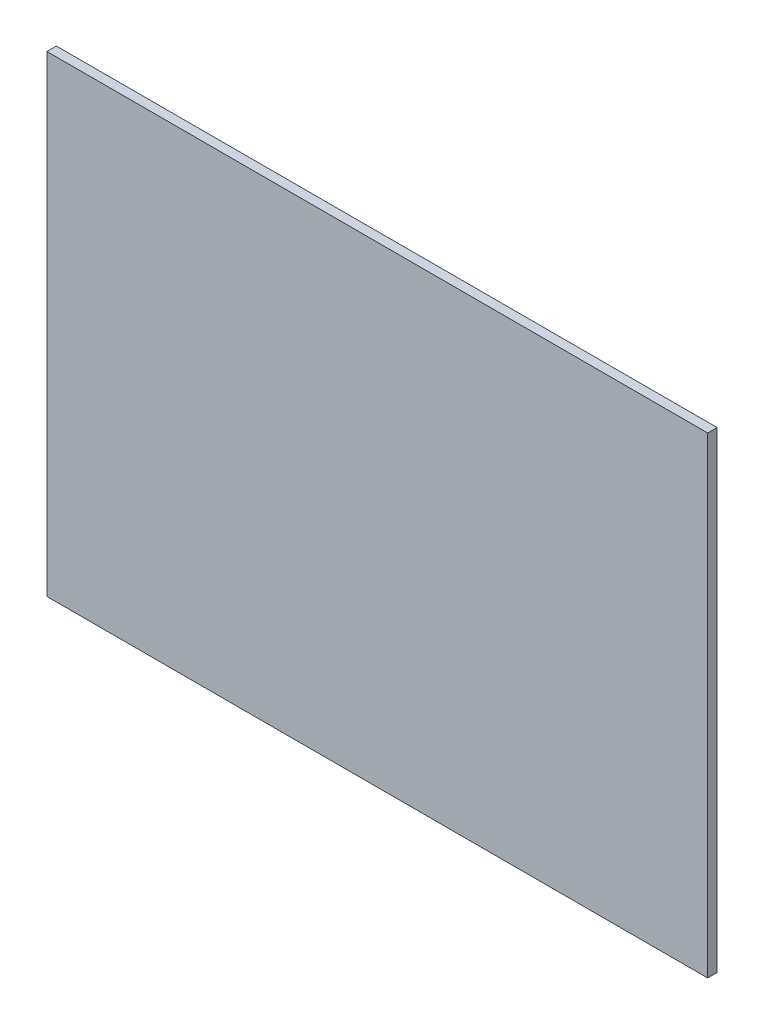
SolidWorks part; units mm, degrees
ref_plane "Front Plane" through (0, 0, 0) normal (0, 0, 1) x (1, 0, 0)
ref_plane "Top Plane" through (0, 0, 0) normal (0, 1, 0) x (1, 0, 0)
ref_plane "Right Plane" through (0, 0, 0) normal (1, 0, 0) x (0, 0, -1)
sketch "Sketch3" plane through (0, 0, 0) normal (0, 0, 1) x (1, 0, 0)
  line L0 (-48.3014, -16.038) -> (161.6986, -16.038)
  line L1 (161.6986, -16.038) -> (161.6986, -166.038)
  line L2 (161.6986, -166.038) -> (-48.3014, -166.038)
  line L3 (-48.3014, -166.038) -> (-48.3014, -16.038)
  line L4 (-48.3014, -166.038) -> (-48.3014, -168.038)
  line L5 (-48.3014, -166.038) -> (161.6986, -166.038)
  line L6 (161.6986, -166.038) -> (161.6986, -168.038)
  line L7 (161.6986, -168.038) -> (-48.3014, -168.038)
  point P8 (0, 0)
  point P9 (0, 0)
  point P10 (0, 0)
  point P11 (0, 0)
  dimension "D1" = 210
  dimension "D2" = 150
  dimension "D3" = 210
  dimension "D4" = 2
  dimension "D5" = 2
extrude "Boss-Extrude3" add sketch "Sketch3" against normal blind 3 contours L3 L0 L1 L2
